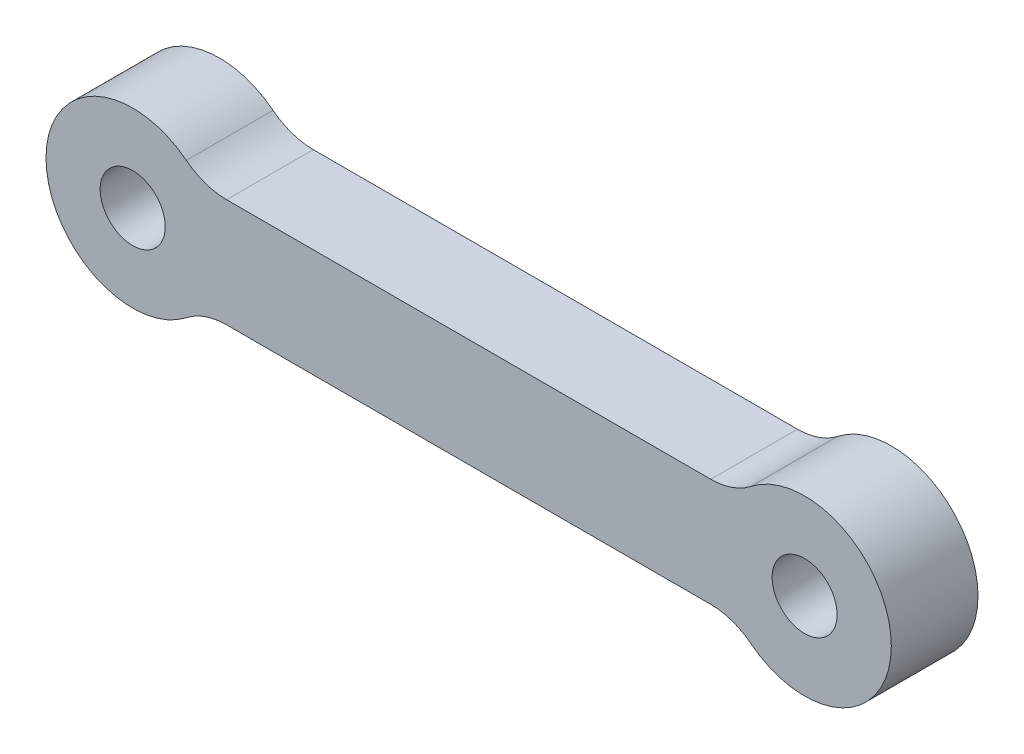
SolidWorks part; units mm, degrees
material "PLA"
ref_plane "Front Plane" through (0, 0, 0) normal (0, 0, 1) x (1, 0, 0)
ref_plane "Top Plane" through (0, 0, 0) normal (0, 1, 0) x (1, 0, 0)
ref_plane "Right Plane" through (0, 0, 0) normal (1, 0, 0) x (0, 0, -1)
sketch "Sketch1" plane through (0, 0, 0) normal (0, 0, 1) x (1, 0, 0)
  line L0 (-15.5, 0) -> (15.5, 0) construction
  line L1 (0, 0) -> (0, 3.4181) construction
  line L3 (-11.1699, 2.5) -> (11.1699, 2.5)
  line L5 (-11.1699, -2.5) -> (11.1699, -2.5)
  line L7 (-12.3775, 2.5) -> (12.3775, -2.5) construction
  line L8 (-12.3775, -2.5) -> (12.3775, 2.5) construction
  circle A0 centre (-15.5, 0) radius 1.5
  arc A1 (-13.0256, 3.1429) -> (-13.0256, -3.1429) centre (-15.5, 0) ccw
  circle A2 centre (15.5, 0) radius 1.5
  arc A3 (13.0256, 3.1429) -> (13.0256, -3.1429) centre (15.5, 0) cw
  arc A4 (11.1699, 2.5) -> (13.0256, 3.1429) centre (11.1699, 5.5) ccw
  arc A5 (11.1699, -2.5) -> (13.0256, -3.1429) centre (11.1699, -5.5) cw
  arc A6 (-13.0256, -3.1429) -> (-11.1699, -2.5) centre (-11.1699, -5.5) cw
  arc A7 (-11.1699, 2.5) -> (-13.0256, 3.1429) centre (-11.1699, 5.5) cw
  point P4 (0, 0)
  dimension "D2" = 3
  dimension "D3" = 8
  dimension "D5" = 3
  dimension "D1" = 31
  dimension "D4" = 5
extrude "Boss-Extrude1" add sketch "Sketch1" along normal blind 4
